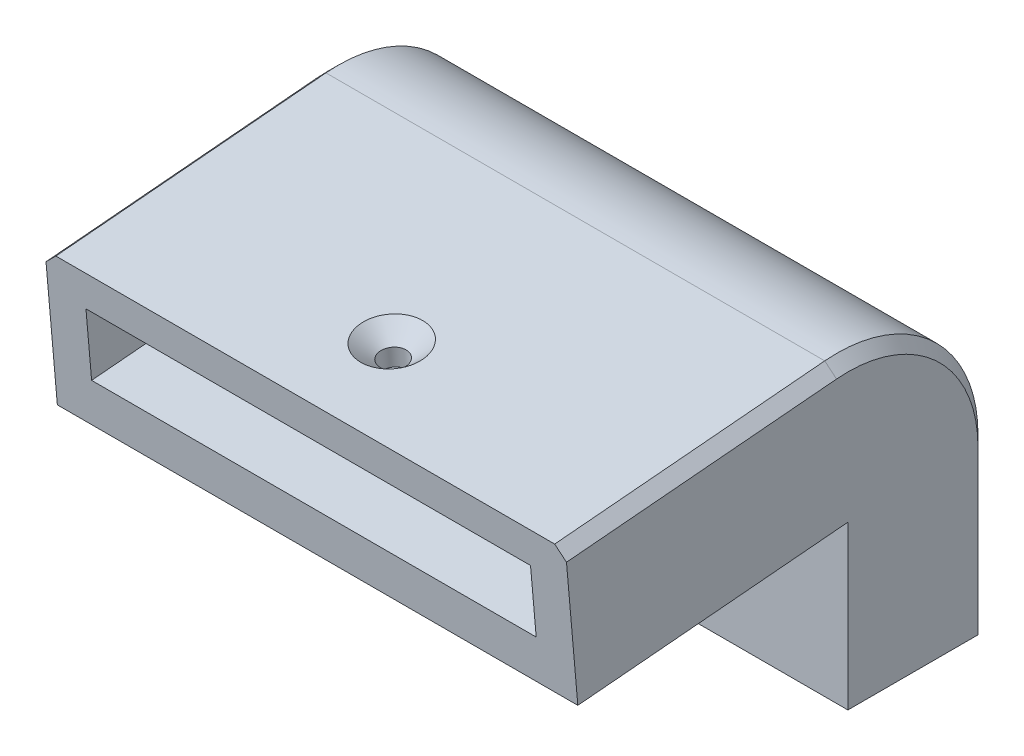
SolidWorks part; units mm, degrees
ref_plane "Front Plane" through (0, 0, 0) normal (0, 0, 1) x (1, 0, 0)
ref_plane "Top Plane" through (0, 0, 0) normal (0, 1, 0) x (1, 0, 0)
ref_plane "Right Plane" through (0, 0, 0) normal (1, 0, 0) x (0, 0, -1)
sketch "Sketch1" plane through (0, 0, 0) normal (0, 1, 0) x (1, 0, 0)
  line L0 (-30.48, 8.255) -> (30.48, 8.255)
  line L1 (-25.4, 3.175) -> (25.4, 3.175)
  line L2 (-25.4, 3.175) -> (-25.4, -3.175)
  line L3 (-25.4, -3.175) -> (25.4, -3.175)
  line L4 (25.4, 3.175) -> (25.4, -3.175)
  line L5 (-25.4, 3.175) -> (25.4, -3.175) construction
  line L6 (-25.4, -3.175) -> (25.4, 3.175) construction
  line L7 (30.48, 8.255) -> (30.48, -8.255)
  line L8 (-30.48, -8.255) -> (30.48, -8.255)
  line L9 (-30.48, 8.255) -> (-30.48, -8.255)
  point P0 (0, 0)
  dimension "D1" = 50.8
  dimension "D2" = 6.35
  dimension "D3" = 5.08
extrude "Boss-Extrude1" add sketch "Sketch1" along normal blind 19.05
sketch "Sketch5" plane through (30.48, 0, 0) normal (1, 0, 0) x (0, 0, -1)
  line L0 (8.255, 19.05) -> (-8.255, 19.05)
  line L1 (-28.6715, 33.8369) -> (-41.3231, 32.73)
  line L2 (-9.6939, 35.4972) -> (-28.6715, 33.8369)
  line L3 (-8.255, 19.05) -> (-39.8842, 16.2828)
  line L8 (-39.8842, 16.2828) -> (-41.3231, 32.73)
  arc A0 (8.255, 19.05) -> (-9.6939, 35.4972) centre (-8.255, 19.05) ccw
  dimension "D1" = 12.7
extrude "Boss-Extrude2" add sketch "Sketch5" against normal up to surface (60.96 mm away) up to face at (-30.48, 9.525, 0)
sketch "Sketch7" plane through (0, -3.3392, 38.1675) normal (0, -0.0872, 0.9962) x (1, 0, 0)
  line L0 (-30.48, 27.952) -> (-25.4, 27.952) construction
  line L1 (-25.4, 31.6241) -> (25.4, 31.6241)
  line L2 (-25.4, 31.6241) -> (-25.4, 25.2741)
  line L3 (-25.4, 25.2741) -> (25.4, 25.2741)
  line L4 (25.4, 31.6241) -> (25.4, 25.2741)
  line L5 (0, 20.1941) -> (0, 25.2741) construction
  line L6 (25.4, 27.952) -> (30.48, 27.952) construction
  line L7 (0, 31.6241) -> (0, 36.207) construction
  point P0 (-1.6836, 26.8959)
  dimension "D1" = 6.35
  dimension "D2" = 50.8
extrude "Cut-Extrude1" cut sketch "Sketch7" against normal blind 19.05
sketch "Sketch8" plane through (0, 36.0692, 3.1556) normal (0, 0.9962, 0.0872) x (1, 0, 0)
  circle A0 centre (0, -28.1533) radius 1.524
  dimension "D1" = 3.048
extrude "Cut-Extrude2" cut sketch "Sketch8" against normal through all
sketch "Sketch9" plane through (0, 0, -8.255) normal (0, 0, -1) x (-1, 0, 0)
  line L1 (-30.48, 0) -> (30.48, 0) construction
  circle A0 centre (0, 10.16) radius 1.5939
  dimension "D1" = 10.16
extrude "Cut-Extrude3" cut sketch "Sketch9" against normal through all
chamfer "Chamfer1" distance 2.1082 angle 41 2 edges at (-1.5939, 10.16, -8.255) (0, 33.4827, 32.72)
sketch "Sketch10" plane through (0, -3.3392, 38.1675) normal (0, -0.0872, 0.9962) x (1, 0, 0)
  line L18 (26.035, 24.6391) -> (26.035, 32.2591)
  line L19 (-26.035, 24.6391) -> (26.035, 24.6391)
  line L20 (-26.035, 32.2591) -> (-26.035, 24.6391)
  line L21 (26.035, 32.2591) -> (-26.035, 32.2591)
  line L22 (26.035, 24.6391) -> (26.035, 32.2591)
  line L23 (-26.035, 24.6391) -> (26.035, 24.6391)
  line L24 (-26.035, 32.2591) -> (-26.035, 24.6391)
  line L25 (26.035, 32.2591) -> (-26.035, 32.2591)
  dimension "D1" = 0.635
extrude "Cut-Extrude4" cut sketch "Sketch10" against normal blind 19.05
sketch "Sketch11" plane through (0, 0, 0) normal (0, -1, 0) x (1, 0, 0)
  line L18 (26.035, -3.81) -> (26.035, 3.81)
  line L19 (-26.035, -3.81) -> (26.035, -3.81)
  line L20 (-26.035, 3.81) -> (-26.035, -3.81)
  line L21 (26.035, 3.81) -> (-26.035, 3.81)
  line L22 (26.035, -3.81) -> (26.035, 3.81)
  line L23 (-26.035, -3.81) -> (26.035, -3.81)
  line L24 (-26.035, 3.81) -> (-26.035, -3.81)
  line L25 (26.035, 3.81) -> (-26.035, 3.81)
  dimension "D1" = 0.635
extrude "Cut-Extrude5" cut sketch "Sketch11" against normal blind 19.05
chamfer "Chamfer2" distance 1.27 angle 45 6 edges at (30.48, 9.525, -8.255) (-30.48, 31.2224, -2.899) (30.48, 31.2224, -2.899) (-30.48, 34.1136, 25.5085) (30.48, 34.1136, 25.5085) (-30.48, 9.525, -8.255)
